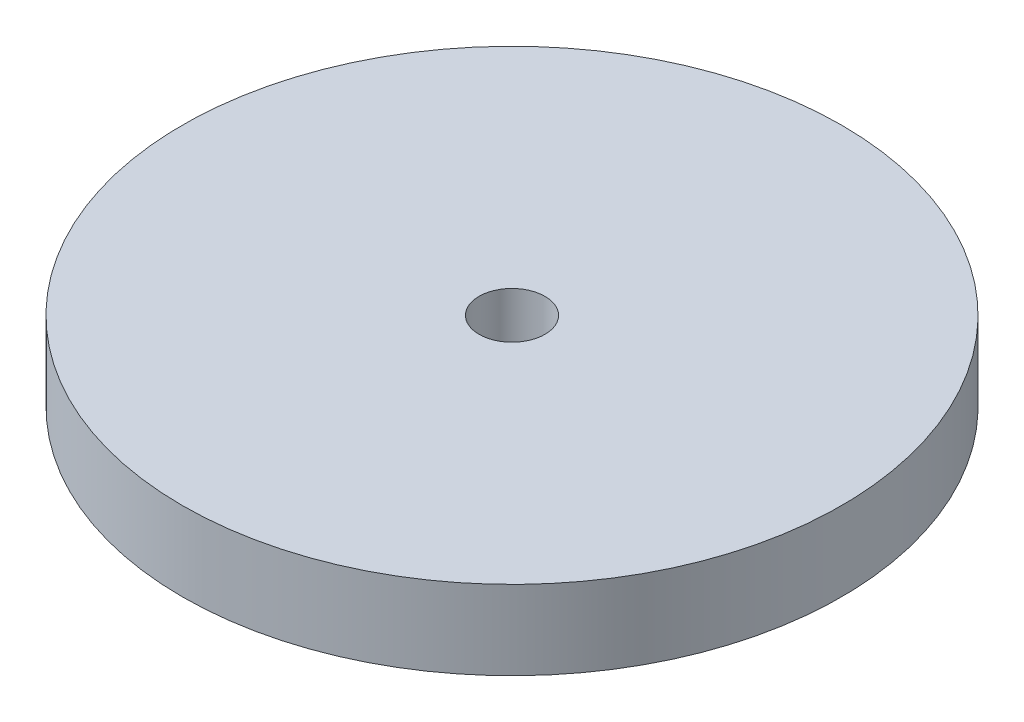
SolidWorks part; units mm, degrees
ref_plane "Front Plane" through (0, 0, 0) normal (0, 0, 1) x (1, 0, 0)
ref_plane "Top Plane" through (0, 0, 0) normal (0, 1, 0) x (1, 0, 0)
ref_plane "Right Plane" through (0, 0, 0) normal (1, 0, 0) x (0, 0, -1)
sketch "Sketch1" plane through (0, 0, 0) normal (0, 1, 0) x (1, 0, 0)
  circle A0 centre (0, 0) radius 12.5
  circle A1 centre (0, 0) radius 125
  dimension "D1" = 25
  dimension "D2" = 250
extrude "Boss-Extrude1" add sketch "Sketch1" along normal mid plane 30
